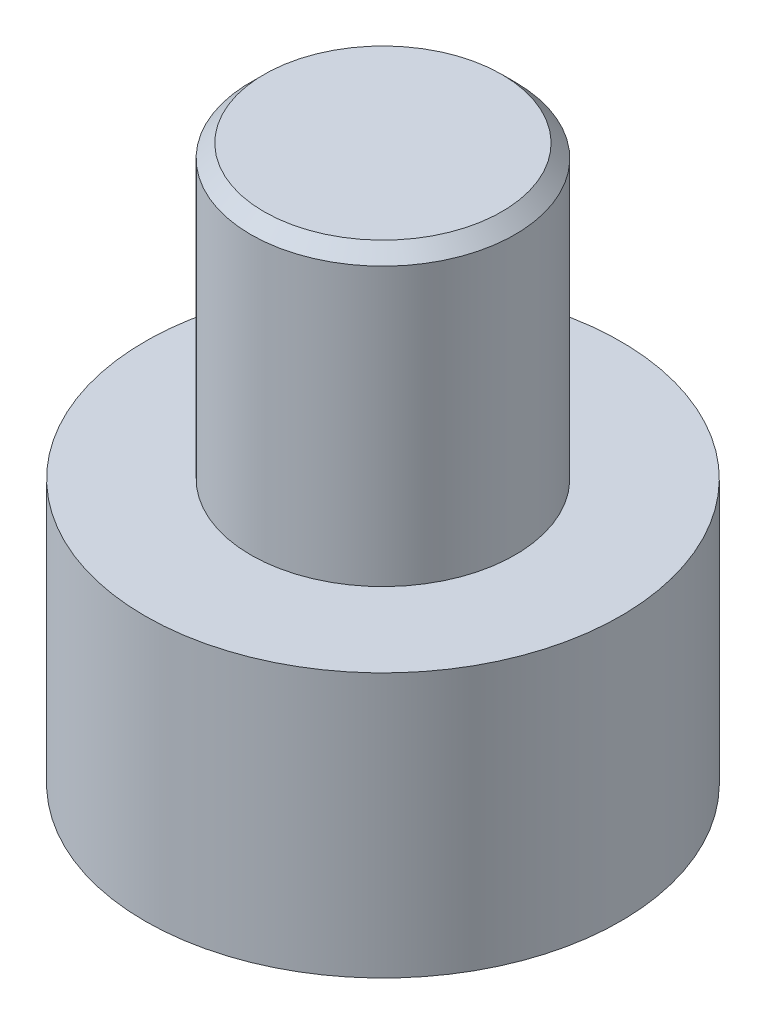
SolidWorks part; units mm, degrees
ref_plane "Přední rovina" through (0, 0, 0) normal (0, 0, 1) x (1, 0, 0)
ref_plane "Horní rovina" through (0, 0, 0) normal (0, 1, 0) x (1, 0, 0)
ref_plane "Pravá rovina" through (0, 0, 0) normal (1, 0, 0) x (0, 0, -1)
sketch "Skica1" plane through (0, 0, 0) normal (0, 0, 1) x (1, 0, 0)
  line L0 (0, 0) -> (-9, 0)
  line L2 (-5, 10) -> (-5, 21)
  line L3 (-5, 21) -> (0, 21)
  line L4 (0, 21) -> (0, 0) construction
  line L5 (0, 0) -> (0, 21)
  line L6 (-9, 0) -> (-9, 10)
  line L7 (-9, 10) -> (-5, 10)
  dimension "D1" = 9
  dimension "D2" = 11
  dimension "D3" = 10
  dimension "D4" = 10
revolve "Rotovat1" add sketch "Skica1" angle 360 about L4
chamfer "Zkosení1" distance 0.5 angle 45 1 edges at (0, 21, 5)
